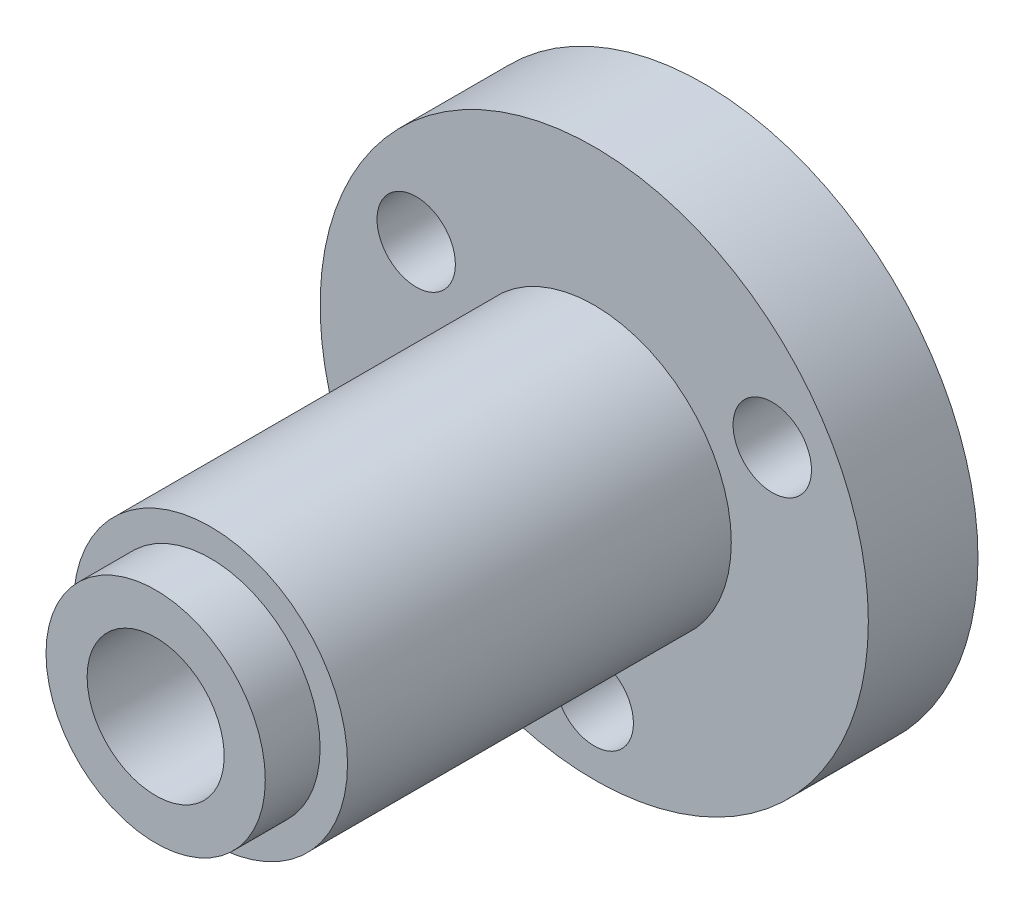
SolidWorks part; units mm, degrees
ref_plane "Front" through (0, 0, 0) normal (0, 0, 1) x (1, 0, 0)
ref_plane "Top" through (0, 0, 0) normal (0, 1, 0) x (1, 0, 0)
ref_plane "Right" through (0, 0, 0) normal (1, 0, 0) x (0, 0, -1)
sketch "Sketch1" plane through (0, 0, 0) normal (0, 0, 1) x (1, 0, 0)
  line L0 (-8.2489, 14.2875) -> (0, 0) construction
  line L1 (0, 0) -> (8.2489, 14.2875) construction
  line L2 (8.2489, 14.2875) -> (-8.2489, 14.2875) construction
  circle A0 centre (0, 0) radius 1.8161
  circle A1 centre (-8.2489, 14.2875) radius 1.8161
  circle A2 centre (8.2489, 14.2875) radius 1.8161
  circle A3 centre (0, 9.525) radius 12.7
  circle A4 centre (0, 9.525) radius 9.525 construction
  dimension "D1" = 3.6322
  dimension "D2" = 19.05
  dimension "D3" = 25.4
extrude "Boss-Extrude1" add sketch "Sketch1" along normal mid plane 5.08
sketch "Sketch2" plane through (0, 0, 2.54) normal (0, 0, 1) x (1, 0, 0)
  circle A0 centre (0, 9.525) radius 6.35
  dimension "D1" = 12.7
extrude "Boss-Extrude2" add sketch "Sketch2" along normal blind 20.32
sketch "Sketch4" plane through (0, 0, -2.54) normal (0, 0, -1) x (-1, 0, 0)
  circle A0 centre (0, 9.525) radius 3.175
  circle A1 centre (0, 9.525) radius 12.7 construction
  dimension "D1" = 6.35
extrude "Cut-Extrude1" cut sketch "Sketch4" against normal through all
sketch "Sketch5" plane through (0, 0, 22.86) normal (0, 0, 1) x (1, 0, 0)
  circle A0 centre (0, 9.525) radius 6.5024
  circle A1 centre (0, 9.525) radius 5.08
  circle A2 centre (0, 9.525) radius 3.175
  circle A3 centre (0, 9.525) radius 3.175 construction
  circle M2 centre (0, 9.525) radius 6.35
  dimension "D1" = 13.0048
  dimension "D2" = 10.16
extrude "Cut-Extrude2" cut sketch "Sketch5" against normal blind 2.54 contours A1 M2
